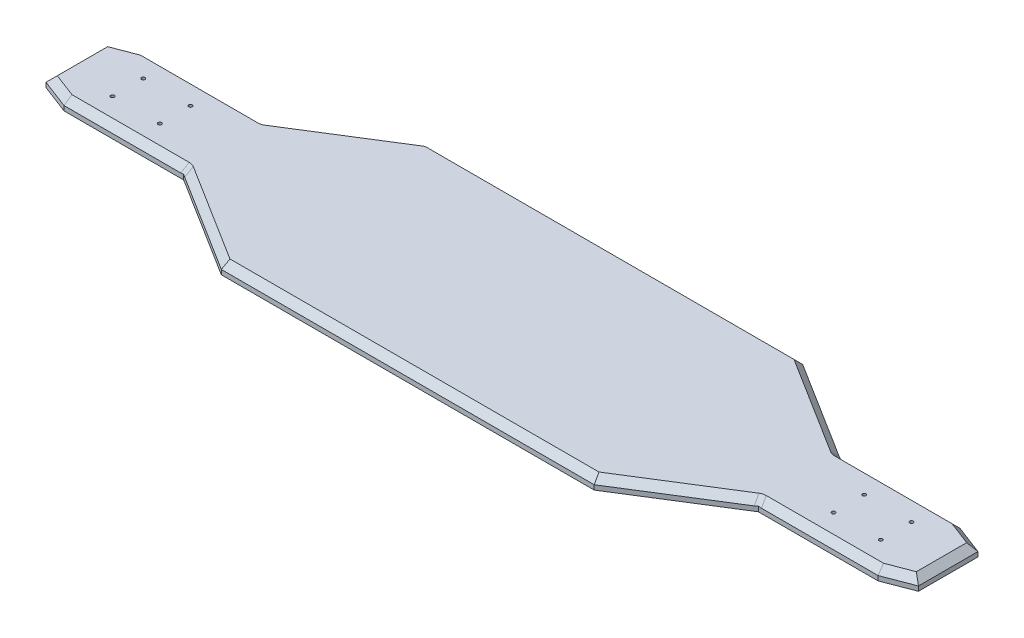
SolidWorks part; units mm, degrees
ref_plane "Front Plane" through (0, 0, 0) normal (0, 0, 1) x (1, 0, 0)
ref_plane "Top Plane" through (0, 0, 0) normal (0, 1, 0) x (1, 0, 0)
ref_plane "Right Plane" through (0, 0, 0) normal (1, 0, 0) x (0, 0, -1)
sketch "Sketch1" plane through (0, 0, 0) normal (0, 1, 0) x (1, 0, 0)
  line L1 (-365.243, 189.9127) -> (135.6482, 189.9127)
  line L2 (-700.7974, 89.9127) -> (-700.7974, 9.9127)
  line L3 (-365.243, -90.0873) -> (135.6482, -90.0873)
  line L6 (-365.243, 189.9127) -> (-500.7974, 104.9127)
  line L7 (-500.7974, 104.9127) -> (-661.5673, 104.9127)
  line L8 (-700.7974, 89.9127) -> (-661.5673, 104.9127)
  line L9 (-700.7974, 9.9127) -> (-661.5673, -5.0873)
  line L10 (-500.7974, -5.0873) -> (-661.5673, -5.0873)
  line L11 (-365.243, -90.0873) -> (-500.7974, -5.0873)
  line L12 (135.6482, -90.0873) -> (271.2026, -5.0873)
  line L13 (135.6482, 189.9127) -> (271.2026, 104.9127)
  line L14 (471.2026, 89.9127) -> (431.9725, 104.9127)
  line L15 (271.2026, 104.9127) -> (431.9725, 104.9127)
  line L16 (271.2026, -5.0873) -> (431.9725, -5.0873)
  line L17 (471.2026, 9.9127) -> (431.9725, -5.0873)
  line L18 (471.2026, 9.9127) -> (471.2026, 89.9127)
  dimension "D4" = 160
  dimension "D7" = 42
extrude "Boss-Extrude1" add sketch "Sketch1" along normal blind 15.24
chamfer "Chamfer1" distance 9 angle 45 16 edges at (-114.7974, 15.24, -189.9127) (-433.0202, 15.24, -147.4127) (-581.1824, 15.24, -104.9127) (-681.1824, 15.24, -97.4127) (-700.7974, 15.24, -49.9127) (-681.1824, 15.24, -2.4127) (-581.1824, 15.24, 5.0873) (-433.0202, 15.24, 47.5873) (-114.7974, 15.24, 90.0873) (203.4254, 15.24, -147.4127) (351.5875, 15.24, -104.9127) (451.5875, 15.24, -97.4127) (471.2026, 15.24, -49.9127) (451.5875, 15.24, -2.4127) (351.5875, 15.24, 5.0873) (203.4254, 15.24, 47.5873)
fillet "Fillet1" radius 20 4 edges at (-499.5032, 10.74, -100.4127) (-499.5032, 10.74, 0.5873) (269.9084, 10.74, 0.5873) (269.9084, 10.74, -100.4127)
sketch "Sketch2" plane through (0, 0, 0) normal (0, -1, 0) x (1, 0, 0)
  line L0 (-700.7974, -49.9127) -> (471.2026, -49.9127) construction
  line L1 (-700.7974, -89.9127) -> (-700.7974, -9.9127) construction
  line L2 (471.2026, -9.9127) -> (471.2026, -89.9127) construction
  line L3 (-114.7974, -189.9127) -> (-114.7974, 90.0873) construction
  line L4 (-630.7974, -29.2752) -> (-567.2974, -29.2752)
  line L5 (-630.7974, -29.2752) -> (-630.7974, -70.5502)
  line L6 (-630.7974, -70.5502) -> (-567.2974, -70.5502)
  line L7 (-567.2974, -29.2752) -> (-567.2974, -70.5502)
  line L8 (135.6482, -189.9127) -> (-365.243, -189.9127) construction
  line L9 (-365.243, 90.0873) -> (135.6482, 90.0873) construction
  circle A0 centre (-630.7974, -29.2752) radius 2.3812
  circle A1 centre (-567.2974, -29.2752) radius 2.3812
  circle A2 centre (-630.7974, -70.5502) radius 2.3812
  circle A3 centre (-567.2974, -70.5502) radius 2.3812
  circle A4 centre (337.7026, -29.2752) radius 2.3812
  circle A5 centre (337.7026, -70.5502) radius 2.3812
  circle A6 centre (401.2026, -70.5502) radius 2.3813
  circle A7 centre (401.2026, -29.2752) radius 2.3813
  dimension "D1" = 63.5
  dimension "D2" = 41.275
  dimension "D3" = 20.6375
  dimension "D4" = 70
extrude "Cut-Extrude1" cut sketch "Sketch2" against normal blind 15.24 contours L5 A2 L6 | L6 A2 L5 | L5 A0 L4 | L4 A0 L5 | L4 A1 L7 | L7 A1 L4 | L7 A3 L6 | L6 A3 L7 | A5 | A4 | A7 | A6
sketch "Sketch4" plane through (0, 15.24, 0) normal (0, 1, 0) x (1, 0, 0)
  line L48 (428.4639, 85.9127) -> (272.6814, 85.9127)
  line L49 (259.8559, 89.6012) -> (130.1839, 170.9127)
  line L50 (130.1839, 170.9127) -> (-359.7787, 170.9127)
  line L51 (-359.7787, 170.9127) -> (-489.4508, 89.6012)
  line L52 (-502.2763, 85.9127) -> (-658.0588, 85.9127)
  line L53 (-658.0588, 85.9127) -> (-681.7974, 76.836)
  line L54 (-681.7974, 76.836) -> (-681.7974, 22.9894)
  line L55 (-681.7974, 22.9894) -> (-658.0588, 13.9127)
  line L56 (-658.0588, 13.9127) -> (-502.2763, 13.9127)
  line L57 (-489.4508, 10.2241) -> (-359.7787, -71.0873)
  line L58 (-359.7787, -71.0873) -> (130.1839, -71.0873)
  line L59 (130.1839, -71.0873) -> (259.8559, 10.2241)
  line L60 (272.6814, 13.9127) -> (428.4639, 13.9127)
  line L61 (428.4639, 13.9127) -> (452.2026, 22.9894)
  line L62 (452.2026, 22.9894) -> (452.2026, 76.836)
  line L63 (452.2026, 76.836) -> (428.4639, 85.9127)
  line L64 (428.4639, 85.9127) -> (272.6814, 85.9127)
  line L65 (259.8559, 89.6012) -> (130.1839, 170.9127)
  line L66 (130.1839, 170.9127) -> (-359.7787, 170.9127)
  line L67 (-359.7787, 170.9127) -> (-489.4508, 89.6012)
  line L68 (-502.2763, 85.9127) -> (-658.0588, 85.9127)
  line L69 (-658.0588, 85.9127) -> (-681.7974, 76.836)
  line L70 (-681.7974, 76.836) -> (-681.7974, 22.9894)
  line L71 (-681.7974, 22.9894) -> (-658.0588, 13.9127)
  line L72 (-658.0588, 13.9127) -> (-502.2763, 13.9127)
  line L73 (-489.4508, 10.2241) -> (-359.7787, -71.0873)
  line L74 (-359.7787, -71.0873) -> (130.1839, -71.0873)
  line L75 (130.1839, -71.0873) -> (259.8559, 10.2241)
  line L76 (272.6814, 13.9127) -> (428.4639, 13.9127)
  line L77 (428.4639, 13.9127) -> (452.2026, 22.9894)
  line L78 (452.2026, 22.9894) -> (452.2026, 76.836)
  line L79 (452.2026, 76.836) -> (428.4639, 85.9127)
  spline S0 degree 3 poles (1192.3143, 2935.5895) (771.7704, 1326.9549) (406.8848, 46.4741) (265.4873, 86.9966) (264.9481, 87.172) (263.8829, 87.561) (263.3591, 87.7738) (98.3086, 161.6588) (811.2294, 2053.4045) (1057.4058, 2978.0547) knots -32.03167 -32.03167 -32.03167 -32.03167 0.5 0.5 0.625 0.625 0.75 0.75 40.673601 40.673601 40.673601 40.673601 only from (272.6814, 85.9127) to (259.8559, 89.6012)
  spline S1 degree 3 poles (-1224.2147, 2992.4455) (-725.9187, 1406.172) (-354.7999, 127.4838) (-496.1216, 86.6977) (-496.6716, 86.5598) (-497.7807, 86.3235) (-498.3375, 86.2255) (-677.4223, 61.1389) (-1078.4148, 2042.5936) (-1361.0709, 2956.7524) knots -32.03167 -32.03167 -32.03167 -32.03167 0.5 0.5 0.625 0.625 0.75 0.75 40.673601 40.673601 40.673601 40.673601 only from (-489.4508, 89.6012) to (-502.2763, 85.9127)
  spline S2 degree 3 poles (-1421.9091, -2835.7642) (-1001.3653, -1227.1296) (-636.4796, 53.3512) (-495.0822, 12.8287) (-494.5429, 12.6533) (-493.4778, 12.2643) (-492.954, 12.0516) (-327.9034, -61.8335) (-1040.8242, -1953.5792) (-1287.0006, -2878.2294) knots -32.03167 -32.03167 -32.03167 -32.03167 0.5 0.5 0.625 0.625 0.75 0.75 40.673601 40.673601 40.673601 40.673601 only from (-502.2763, 13.9127) to (-489.4508, 10.2241)
  spline S3 degree 3 poles (994.6199, -2892.6202) (496.3239, -1306.3467) (125.2051, -27.6585) (266.5267, 13.1276) (267.0768, 13.2655) (268.1858, 13.5018) (268.7426, 13.5998) (447.8274, 38.6864) (848.82, -1942.7683) (1131.476, -2856.9271) knots -32.03167 -32.03167 -32.03167 -32.03167 0.5 0.5 0.625 0.625 0.75 0.75 40.673601 40.673601 40.673601 40.673601 only from (259.8559, 10.2241) to (272.6814, 13.9127)
  spline S4 degree 3 poles (272.6814, 85.9127) (270.4113, 85.9127) (268.1935, 86.2211) (265.4873, 86.9966) (264.9481, 87.172) (263.8829, 87.561) (263.3591, 87.7738) (261.8137, 88.4656) (260.8178, 88.9981) (259.8559, 89.6012) knots 0 0 0 0 0.5 0.5 0.625 0.625 0.75 0.75 1 1 1 1
  spline S5 degree 3 poles (-489.4508, 89.6012) (-491.3741, 88.3952) (-493.4169, 87.4783) (-496.1216, 86.6977) (-496.6716, 86.5598) (-497.7807, 86.3235) (-498.3375, 86.2255) (-500.0143, 85.9906) (-501.141, 85.9127) (-502.2763, 85.9127) knots 0 0 0 0 0.5 0.5 0.625 0.625 0.75 0.75 1 1 1 1
  spline S6 degree 3 poles (-502.2763, 13.9127) (-500.0061, 13.9127) (-497.7883, 13.6043) (-495.0822, 12.8287) (-494.5429, 12.6533) (-493.4778, 12.2643) (-492.954, 12.0516) (-491.4085, 11.3597) (-490.4126, 10.8272) (-489.4508, 10.2241) knots 0 0 0 0 0.5 0.5 0.625 0.625 0.75 0.75 1 1 1 1
  spline S7 degree 3 poles (259.8559, 10.2241) (261.7792, 11.4301) (263.822, 12.3471) (266.5267, 13.1276) (267.0768, 13.2655) (268.1858, 13.5018) (268.7426, 13.5998) (270.4195, 13.8347) (271.5461, 13.9127) (272.6814, 13.9127) knots 0 0 0 0 0.5 0.5 0.625 0.625 0.75 0.75 1 1 1 1
  dimension "D1" = 10
